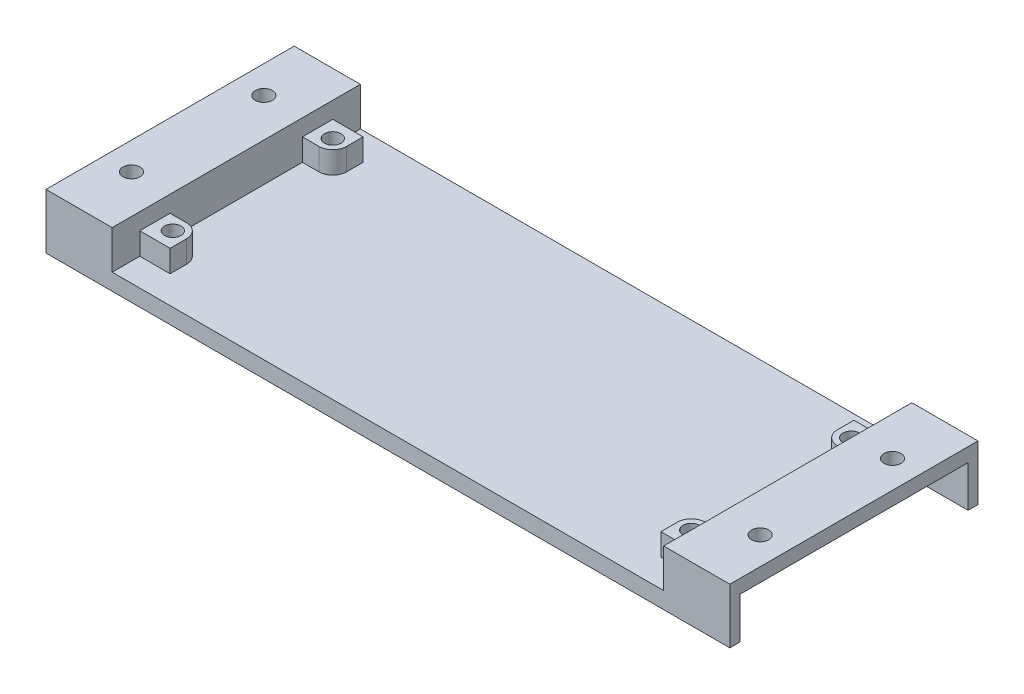
SolidWorks part; units mm, degrees
ref_plane "Front Plane" through (0, 0, 0) normal (0, 0, 1) x (1, 0, 0)
ref_plane "Top Plane" through (0, 0, 0) normal (0, 1, 0) x (1, 0, 0)
ref_plane "Right Plane" through (0, 0, 0) normal (1, 0, 0) x (0, 0, -1)
sketch "Sketch2" plane through (0, 0, 0) normal (0, 1, 0) x (1, 0, 0)
  line L7 (-62, 22.5) -> (62, 22.5)
  line L8 (-62, 22.5) -> (-62, -22.5)
  line L9 (-62, -22.5) -> (62, -22.5)
  line L10 (62, 22.5) -> (62, -22.5)
  line L11 (-62, 22.5) -> (62, -22.5) construction
  line L12 (-62, -22.5) -> (62, 22.5) construction
  dimension "D3" = 45
  dimension "D4" = 124
extrude "Boss-Extrude3" add sketch "Sketch2" along normal blind 10
sketch "Sketch4" plane through (0, 10, 0) normal (0, 1, 0) x (1, 0, 0)
  line L1 (-50, 22.5) -> (50, 22.5)
  line L2 (-50, 22.5) -> (-50, -22.5)
  line L3 (-50, -22.5) -> (50, -22.5)
  line L4 (50, 22.5) -> (50, -22.5)
  line L5 (-50, 22.5) -> (50, -22.5) construction
  line L6 (-50, -22.5) -> (50, 22.5) construction
  point P0 (0, 0)
  dimension "D1" = 45
  dimension "D2" = 100
extrude "Cut-Extrude1" cut sketch "Sketch4" against normal blind 7
sketch "Sketch5" plane through (0, 10, 0) normal (0, 1, 0) x (1, 0, 0)
  line L0 (-62, 0) -> (62, 0) construction
  line L1 (-62, 22.5) -> (-62, -22.5) construction
  line L2 (62, -22.5) -> (62, 22.5) construction
  line L3 (0, 0) -> (0, 22.5) construction
  line L8 (50, 22.5) -> (-50, 22.5) construction
  circle A0 centre (-57, 12) radius 1.55
  circle A1 centre (-57, -12) radius 1.55
  circle A2 centre (57, -12) radius 1.55
  circle A3 centre (57, 12) radius 1.55
  dimension "D1" = 3.1
  dimension "D2" = 12
  dimension "D3" = 5
extrude "Cut-Extrude2" cut sketch "Sketch5" against normal up to next
sketch "Sketch6" plane through (0, 0, 0) normal (0, -1, 0) x (1, 0, 0)
  line L0 (0, 22.5) -> (0, -22.5) construction
  line L1 (-62, 22.5) -> (62, 22.5) construction
  line L2 (62, -22.5) -> (-62, -22.5) construction
  line L3 (-62, -22.5) -> (-62, 22.5) construction
  line L4 (-62, 20.7) -> (-51.8, 20.7)
  line L5 (-62, 20.7) -> (-62, -20.7)
  line L6 (-62, -20.7) -> (-51.8, -20.7)
  line L7 (-51.8, 20.7) -> (-51.8, -20.7)
  line L8 (-62, 20.7) -> (-51.8, -20.7) construction
  line L9 (-62, -20.7) -> (-51.8, 20.7) construction
  line L10 (62, -20.7) -> (51.8, 20.7) construction
  line L11 (62, 20.7) -> (51.8, -20.7) construction
  line L12 (51.8, 20.7) -> (51.8, -20.7)
  line L13 (62, -20.7) -> (51.8, -20.7)
  line L14 (62, 20.7) -> (62, -20.7)
  line L15 (62, 20.7) -> (51.8, 20.7)
  point P6 (-56.9, 0)
  point P13 (-62, 0)
  point P18 (56.9, 0)
  dimension "D1" = 41.4
  dimension "D2" = 10.2
extrude "Cut-Extrude3" cut sketch "Sketch6" against normal blind 7.5
sketch "Sketch7" plane through (0, 3, 0) normal (0, 1, 0) x (1, 0, 0)
  line L2 (0, 22.5) -> (0, -22.5) construction
  line L7 (50, 22.5) -> (-50, 22.5) construction
  line L8 (-50, -22.5) -> (50, -22.5) construction
  line L10 (-50, 0) -> (50, 0) construction
  line L12 (-50, 22.5) -> (-50, -22.5) construction
  line L13 (50, -22.5) -> (50, 22.5) construction
  line L14 (-44.5, -17.5) -> (-44.5, -12)
  line L15 (-50, 17.5) -> (50, 17.5)
  line L16 (-50, 17.5) -> (-50, -17.5)
  line L17 (-50, -17.5) -> (50, -17.5)
  line L18 (50, 17.5) -> (50, -17.5)
  line L19 (-50, 17.5) -> (50, -17.5) construction
  line L20 (-50, -17.5) -> (50, 17.5) construction
  line L21 (-50, 17.5) -> (-44.5, 17.5)
  line L22 (-50, 17.5) -> (-50, 12)
  line L23 (-50, 12) -> (-44.5, 12)
  line L24 (-44.5, 17.5) -> (-44.5, 12)
  line L25 (-50, -12) -> (-44.5, -12)
  line L26 (-50, -17.5) -> (-50, -12)
  line L27 (-50, -17.5) -> (-44.5, -17.5)
  line L35 (50, 17.5) -> (50, -17.5)
  line L37 (50, -17.5) -> (44.5, -17.5)
  line L38 (50, -17.5) -> (50, -12)
  line L39 (50, -12) -> (44.5, -12)
  line L40 (44.5, -17.5) -> (44.5, -12)
  line L41 (44.5, 17.5) -> (44.5, 12)
  line L42 (50, 12) -> (44.5, 12)
  line L43 (50, 17.5) -> (50, 12)
  line L44 (50, 17.5) -> (44.5, 17.5)
  circle A8 centre (-47, 14.5) radius 1.5
  circle A9 centre (-47, 14.5) radius 2.5
  circle A10 centre (-47, -14.5) radius 2.5
  circle A11 centre (-47, -14.5) radius 1.5
  circle A16 centre (47, -14.5) radius 1.5
  circle A17 centre (47, -14.5) radius 2.5
  circle A18 centre (47, 14.5) radius 2.5
  circle A19 centre (47, 14.5) radius 1.5
  point P12 (0, 0)
  dimension "D3" = 3
  dimension "D2" = 3
  dimension "D5" = 5
  dimension "D1" = 35
  dimension "D4" = 3
  dimension "D6" = 5.5
  dimension "D7" = 5.5
extrude "Boss-Extrude4" add sketch "Sketch7" along normal blind 4
